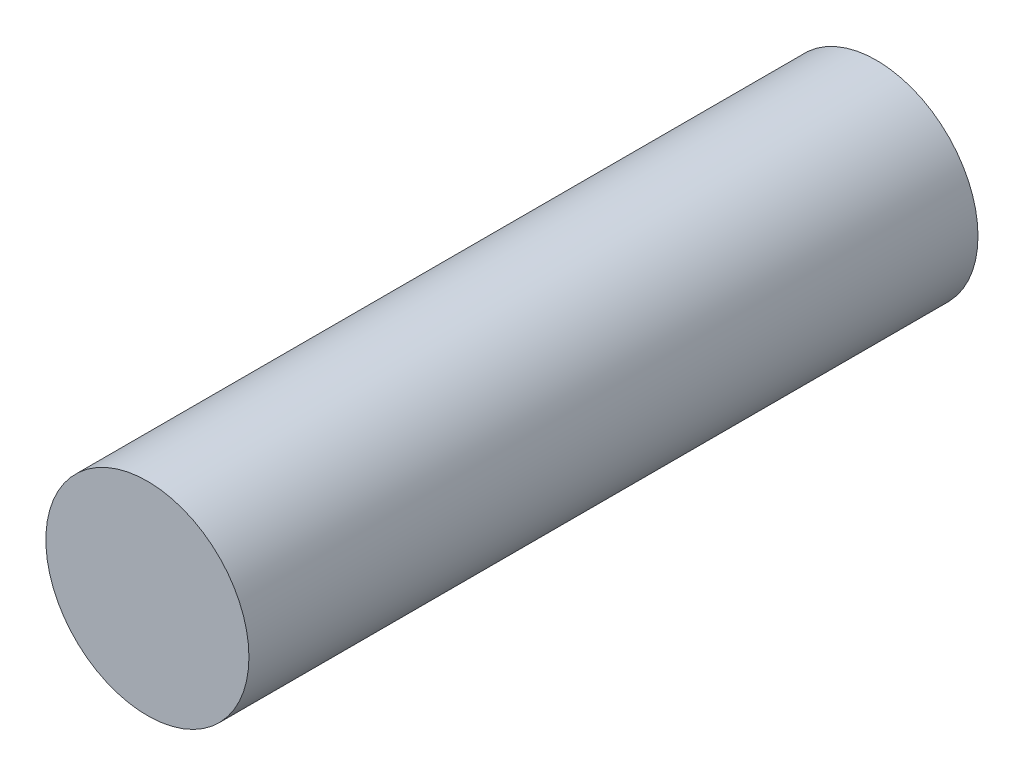
SolidWorks part; units mm, degrees
ref_plane "Front Plane" through (0, 0, 0) normal (0, 0, 1) x (1, 0, 0)
ref_plane "Top Plane" through (0, 0, 0) normal (0, 1, 0) x (1, 0, 0)
ref_plane "Right Plane" through (0, 0, 0) normal (1, 0, 0) x (0, 0, -1)
sketch "Sketch2" plane through (0, 0, 0) normal (0, 0, 1) x (1, 0, 0)
  circle A0 centre (0, 0) radius 0.975
  dimension "D1" = 1.95
extrude "Boss-Extrude1" add sketch "Sketch2" against normal blind 7
